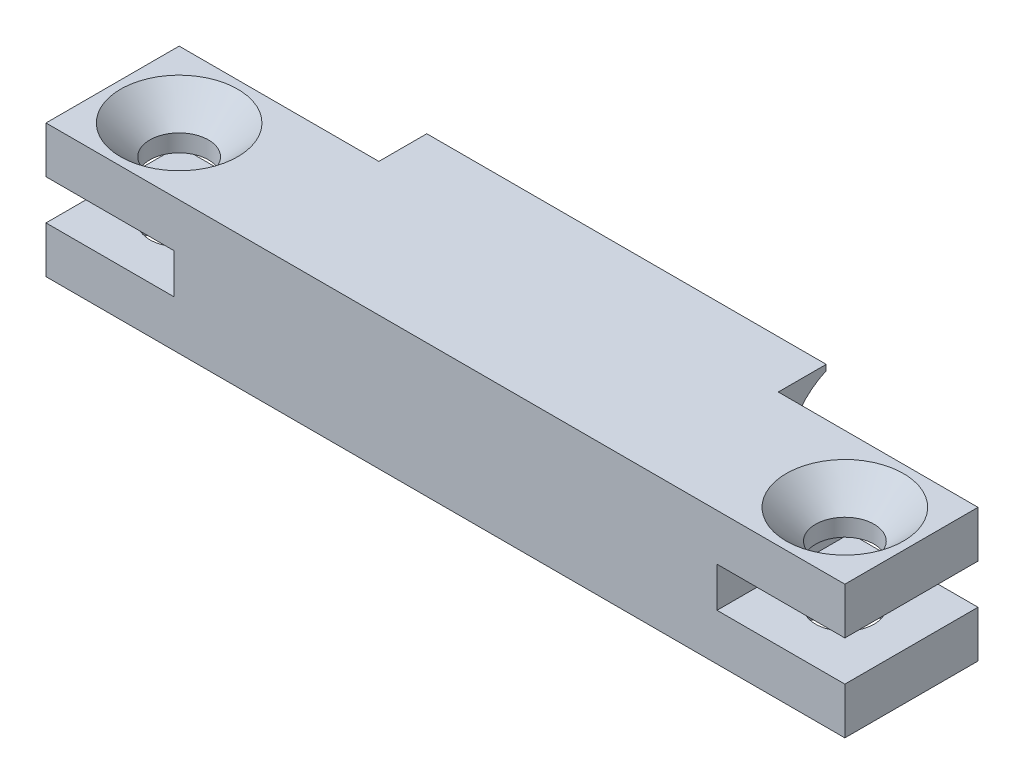
SolidWorks part; units mm, degrees
material "ПК/АБС"
ref_plane "Спереди" through (0, 0, 0) normal (0, 0, 1) x (1, 0, 0)
ref_plane "Сверху" through (0, 0, 0) normal (0, 1, 0) x (1, 0, 0)
ref_plane "Справа" through (0, 0, 0) normal (1, 0, 0) x (0, 0, -1)
sketch "Эскиз1" plane through (0, 0, 0) normal (1, 0, 0) x (0, 0, -1)
  line L0 (0, 2.5) -> (0, -2.5)
  line L5 (0, -2.5) -> (7.8, -2.5)
  line L6 (0, 2.5) -> (7.8, 2.5)
  line L7 (7.8, 3.4493) -> (7.8, -3.5457) construction
  arc A0 (7.8, 2.5) -> (7.8, -2.5) centre (7.8, 0) ccw
  point P2 (5.3, 0)
  dimension "D1" = 5
  dimension "D2" = 2.5
  dimension "D3" = 5.3
extrude "Бобышка-Вытянуть1" add sketch "Эскиз1" along normal blind 15
sketch "Эскиз2" plane through (15, 0, 0) normal (1, 0, 0) x (0, 0, -1)
  line L0 (7.8, 2.5) -> (7.8, -2.5) construction
  line L1 (0, 0) -> (11.8376, 0) construction
  line L3 (7.8, 2.5) -> (6.8, 2.5)
  line L4 (7.8, 2.5) -> (7.8, 1.5)
  line L5 (7.8, 1.5) -> (6.8, 1.5)
  line L6 (6.8, 2.5) -> (6.8, 1.5)
  line L7 (7.8, -2.5) -> (7.8, -1.5)
  line L8 (7.8, -1.5) -> (6.8, -1.5)
  line L9 (6.8, -2.5) -> (6.8, -1.5)
  line L10 (7.8, -2.5) -> (6.8, -2.5)
  arc A0 (7.8, 2.5) -> (7.8, -2.5) centre (7.8, 0) ccw construction
  dimension "D1" = 1
  dimension "D2" = 1
extrude "Вырез-Вытянуть1" cut sketch "Эскиз2" against normal blind 15
sketch "Эскиз6" plane through (0, 0, 0) normal (-1, 0, 0) x (0, 0, 1)
  line L0 (0, 2.5) -> (0, -2.5) construction
  line L1 (0, 2.5) -> (-5, 2.5)
  line L2 (0, 2.5) -> (0, 0.75)
  line L3 (0, 0.75) -> (-5, 0.75)
  line L4 (-5, 2.5) -> (-5, 0.75)
  line L5 (0, -2.5) -> (-5, -2.5)
  line L6 (0, -2.5) -> (0, -0.75)
  line L7 (0, -0.75) -> (-5, -0.75)
  line L8 (-5, -2.5) -> (-5, -0.75)
  line L9 (0, 2.5) -> (-6.8, 2.5) construction
  line L10 (0, -2.5) -> (-6.8, -2.5) construction
  point P10 (0, 0)
  dimension "D1" = 1.5
  dimension "D2" = 0.75
  dimension "D3" = 5
  dimension "D4" = 5
extrude "Бобышка-Вытянуть2" add sketch "Эскиз6" along normal blind 7.5
sketch "Эскиз7" plane through (15, 0, 0) normal (1, 0, 0) x (0, 0, -1)
  line L0 (0, 0.75) -> (0, -0.75) construction
  line L1 (0, 2.5) -> (5, 2.5)
  line L2 (0, 2.5) -> (0, 0.75)
  line L3 (0, 0.75) -> (5, 0.75)
  line L4 (5, 2.5) -> (5, 0.75)
  line L5 (0, -2.5) -> (5, -2.5)
  line L6 (0, -2.5) -> (0, -0.75)
  line L7 (0, -0.75) -> (5, -0.75)
  line L8 (5, -2.5) -> (5, -0.75)
  line L9 (0, 2.5) -> (6.8, 2.5) construction
  line L10 (0, -2.5) -> (6.8, -2.5) construction
  point P10 (0, 0)
  dimension "D1" = 1.5
  dimension "D2" = 0.75
  dimension "D3" = 5
  dimension "D4" = 5
extrude "Бобышка-Вытянуть3" add sketch "Эскиз7" along normal blind 7.5
hole_wizard "Зенковка для винта с полупотайной головкой M21" positions "Эскиз4" profile "Эскиз3" countersink size "M2" standard "ISO" end condition through all
sketch "Эскиз4" plane through (0, 2.5, 0) normal (0, 1, 0) x (1, 0, 0)
  line L3 (-7.5, 0) -> (-7.5, 5) construction
  line L4 (22.5, 0) -> (-7.5, 0) construction
  line L5 (22.5, 5) -> (22.5, 0) construction
  point P0 (20, 2.5)
  point P2 (-5, 2.5)
  point P21 (18.0999, 0)
  dimension "D1" = 2.5
  dimension "D2" = 2.5
  dimension "D3" = 2.5
  dimension "D4" = 2.5
sketch "Эскиз3" plane through (20, 2.5, -2.5) normal (1, 0, 0) x (0, 0, 1)
  line L0 (0, 0) -> (0, 5)
  line L1 (0, 5) -> (1.1, 5)
  line L2 (1.1, 5) -> (1.1, 1.1)
  line L3 (1.1, 1.1) -> (2.2, 0)
  line L5 (2.2, 0) -> (0, 0)
  line L6 (-1.1, 1.1) -> (-2.2, 0) construction
  line L11 (0, -6.35) -> (0, 107.95) construction
  dimension "Диаметр сквозного отверстия" = 2.2
  dimension "Глубина сквозного отверстия" = 5
  dimension "Диаметр передней зенковки" = 4.4
  dimension "Угол передней зенковки" = 90
sketch "Эскиз5" plane through (0, -2.5, 0) normal (0, -1, 0) x (1, 0, 0)
  line L2 (-6.1789, -0.4581) -> (-7.3577, -2.5)
  line L3 (-7.3577, -2.5) -> (-6.1789, -4.5419)
  line L4 (-6.1789, -4.5419) -> (-3.8211, -4.5419)
  line L5 (-3.8211, -4.5419) -> (-2.6423, -2.5)
  line L6 (-2.6423, -2.5) -> (-3.8211, -0.4581)
  line L7 (7.5, 0) -> (7.5, -6.8) construction
  line L9 (21.1789, -4.5419) -> (18.8211, -4.5419)
  line L10 (18.8211, -4.5419) -> (17.6423, -2.5)
  line L11 (22.3577, -2.5) -> (21.1789, -4.5419)
  line L12 (21.1789, -0.4581) -> (22.3577, -2.5)
  line L13 (-7.5, -5) -> (-7.5, 0) construction
  line L14 (-7.5, -5) -> (0, -5) construction
  line L15 (-3.8211, -0.4581) -> (-6.1789, -0.4581)
  line L17 (2.4986, -0.5081) -> (1.4118, -0.5081) construction
  line L18 (18.8211, -0.4581) -> (21.1789, -0.4581)
  line L19 (17.6423, -2.5) -> (18.8211, -0.4581)
  line L21 (0, -6.8) -> (15, -6.8) construction
  line L22 (22.5, 0) -> (-7.5, 0) construction
  circle A0 centre (-5, -2.5) radius 2.0419 construction
  dimension "D1" = 2.5
  dimension "D2" = 2.5
extrude "Вырез-Вытянуть2" cut sketch "Эскиз5" against normal blind 1.2
sketch "Эскиз8" plane through (0, 0, 0) normal (0, 0, 1) x (1, 0, 0)
  line L0 (-7.5, -0.75) -> (0, -0.75) construction
  line L1 (0, 0.75) -> (-2.7, 0.75)
  line L2 (0, 0.75) -> (0, -0.75)
  line L3 (0, -0.75) -> (-2.7, -0.75)
  line L4 (-2.7, 0.75) -> (-2.7, -0.75)
  line L5 (-7.5, 0.75) -> (0, 0.75) construction
  line L6 (22.5, -0.75) -> (15, -0.75) construction
  line L7 (15, 0.75) -> (17.7, 0.75)
  line L8 (15, 0.75) -> (15, -0.75)
  line L9 (15, -0.75) -> (17.7, -0.75)
  line L10 (17.7, 0.75) -> (17.7, -0.75)
  dimension "D1" = 2.7
  dimension "D2" = 2.7
extrude "Бобышка-Вытянуть4" add sketch "Эскиз8" against normal blind 5
